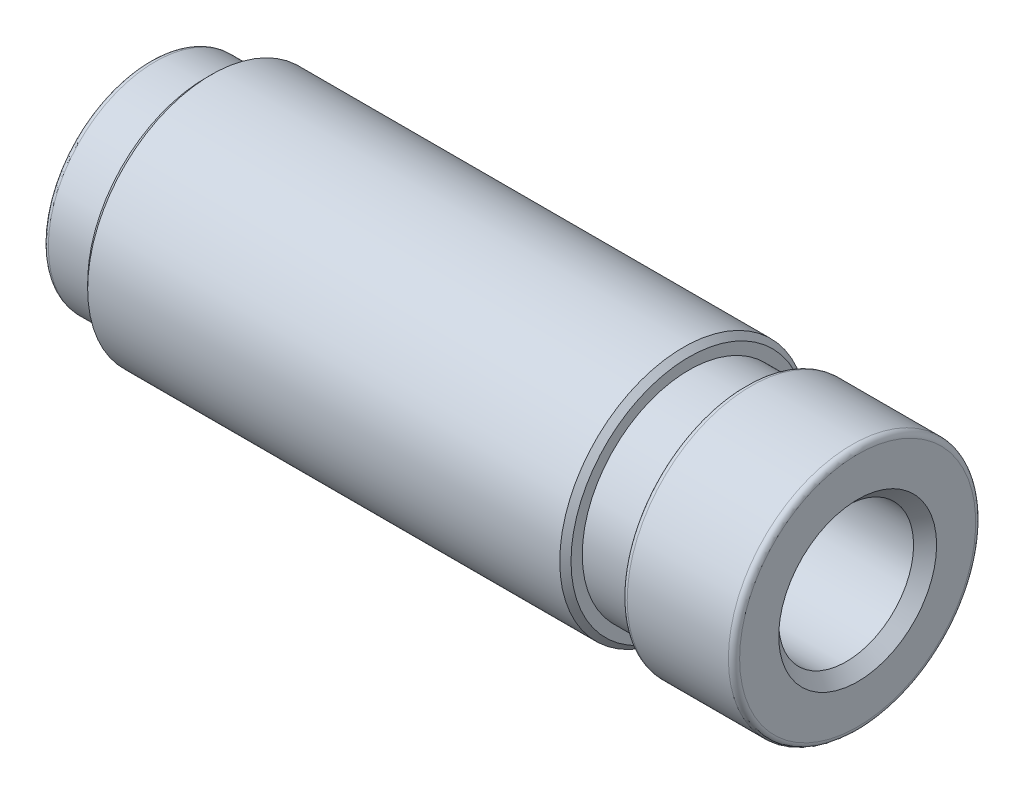
SolidWorks part; units mm, degrees
ref_plane "Plano frontal" through (0, 0, 0) normal (0, 0, 1) x (1, 0, 0)
ref_plane "Plano superior" through (0, 0, 0) normal (0, 1, 0) x (1, 0, 0)
ref_plane "Plano direito" through (0, 0, 0) normal (1, 0, 0) x (0, 0, -1)
sketch "Esboço1" plane through (0, 0, 0) normal (0, 0, 1) x (1, 0, 0)
  line L0 (0, 0) -> (63, 0)
  line L1 (63, 0) -> (63, 11)
  line L2 (63, 11) -> (53, 11)
  line L3 (53, 11) -> (53, 9.5)
  line L4 (53, 9.5) -> (48, 9.5)
  line L5 (48, 9.5) -> (48, 11)
  line L6 (48, 11) -> (5, 11)
  line L7 (5, 11) -> (5, 9.5)
  line L8 (5, 9.5) -> (0, 9.5)
  line L9 (0, 9.5) -> (0, 0)
  point P2 (48, 10.25)
  point P11 (53, 10.25)
  point P13 (2.5, 9.5)
  point P14 (50.5, 9.5)
  dimension "D1" = 10
  dimension "D2" = 5
  dimension "D3" = 5
  dimension "D4" = 1.5
  dimension "D5" = 1.5
  dimension "D6" = 63
  dimension "D7" = 11
revolve "Revolução1" add sketch "Esboço1" angle 360 about L0
cosmetic thread "Representação de rosca5" parameters "D2"=19.252
hole_wizard "Furo roscado de M141" positions "Esboço4" profile "Esboço3" tap size "M14" standard "DIN"
sketch "Esboço4" plane through (63, 0, 0) normal (1, 0, 0) x (0, 0, -1)
  point P0 (0, 0)
sketch "Esboço3" plane through (63, 0, 0) normal (0, 1, 0) x (0, 0, -1)
  line L0 (0, 0) -> (0, 53.6052)
  line L1 (0, 53.6052) -> (6, 50)
  line L2 (6, 50) -> (6, 1.025)
  line L3 (6, 1.025) -> (7.025, 0)
  line L5 (7.025, 0) -> (0, 0)
  line L6 (-6, 1.025) -> (-7.025, 0) construction
  line L10 (0, 53.6052) -> (-6, 50) construction
  line L11 (0, -6.35) -> (0, 107.95) construction
  dimension "Tap Drill Dia." = 12
  dimension "Tap Drill Depth" = 50
  dimension "Near C'Sink Dia." = 14.05
  dimension "Near C'Sink Angle" = 90
  dimension "Drill Angle" = 118
cosmetic thread "Rosca de furo1" parameters "D1"=50, "D2"=14
cosmetic thread "Representação de rosca9" parameters "D2"=14
hole_wizard "Furo1" positions "Esboço5" profile "Esboço6" legacy end condition through all
sketch "Esboço5" plane through (0, 0, 0) normal (-1, 0, 0) x (0, 0, 1)
  point P0 (0, 0)
sketch "Esboço6" plane through (0, 0, 0) normal (0, 1, 0) x (0, 0, 1)
  line L0 (0, 0) -> (0, 63)
  line L1 (0, 63) -> (4.84, 63)
  line L2 (4.84, 63) -> (4.84, 0)
  line L3 (4.84, 0) -> (0, 0)
  line L4 (0, 110) -> (0, -10) construction
  dimension "Diameter" = 9.68
  dimension "Depth" = 63
fillet "Filete1" radius 0.5 3 edges at (63, 0, 11) (53, 0, 11) (0, 0, 9.5)
fillet "Filete2" radius 1.5 1 edges at (0, 0, 4.84)
chamfer "Chanfro1" distance 0.5 angle 45 2 edges at (48, 0, 11) (5, 0, 11)
